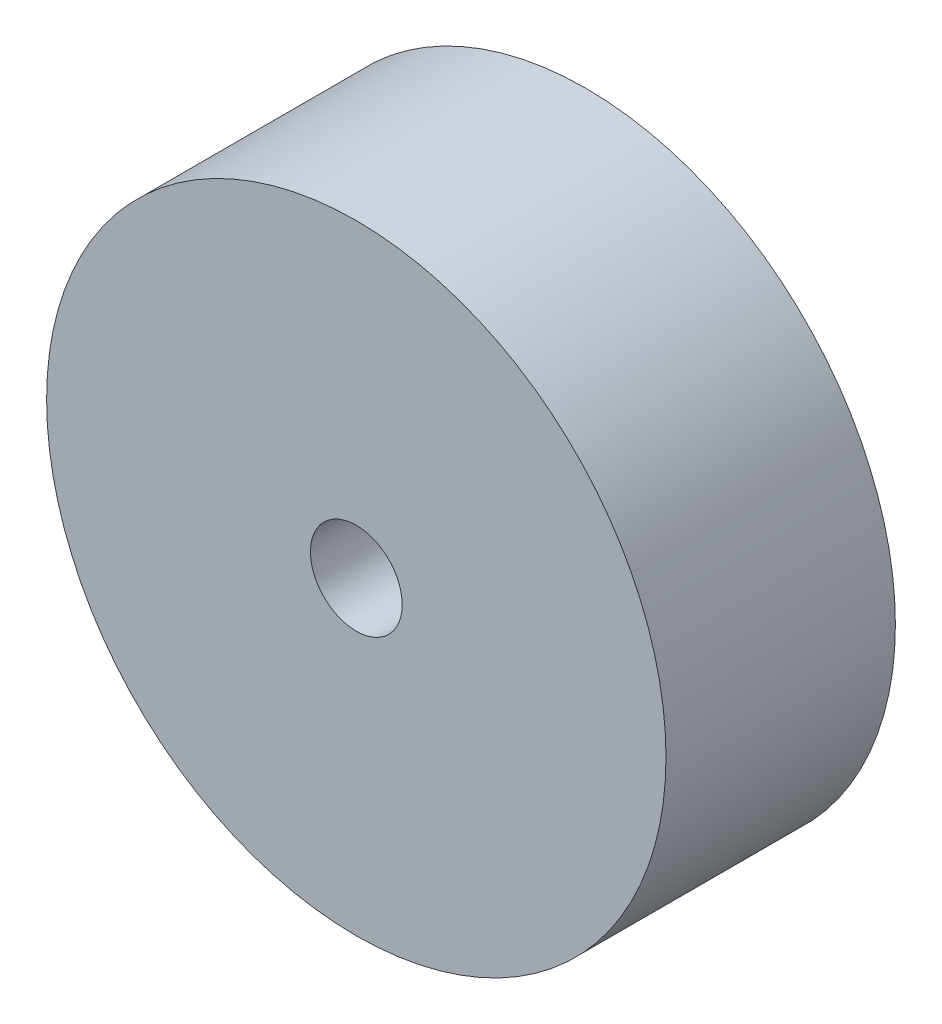
SolidWorks part; units mm, degrees
ref_plane "Front Plane" through (0, 0, 0) normal (0, 0, 1) x (1, 0, 0)
ref_plane "Top Plane" through (0, 0, 0) normal (0, 1, 0) x (1, 0, 0)
ref_plane "Right Plane" through (0, 0, 0) normal (1, 0, 0) x (0, 0, -1)
sketch "Esquisse2" plane through (0, 0, 0) normal (0, 0, 1) x (1, 0, 0)
  circle A0 centre (0, 0) radius 6.75
  circle A1 centre (0, 0) radius 1
  dimension "D1" = 13.5
  dimension "D2" = 2
extrude "Boss.-Extru.1" add sketch "Esquisse2" along normal blind 5
